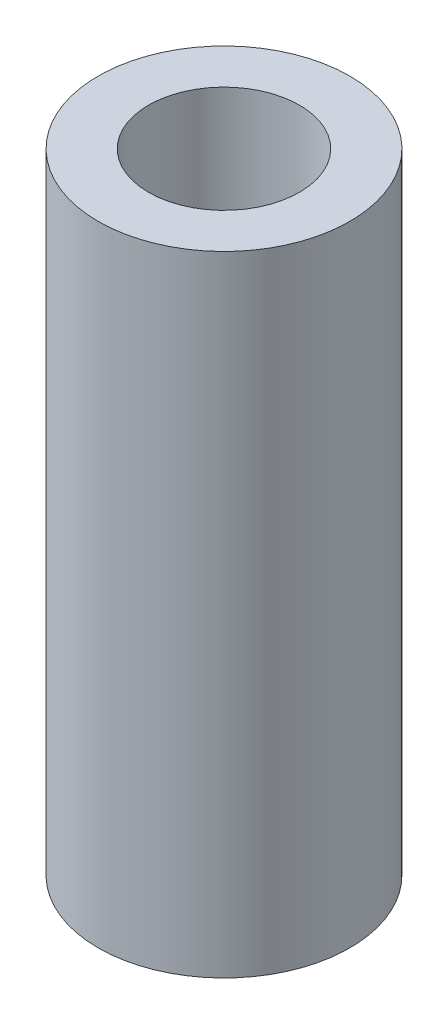
SolidWorks part; units mm, degrees
ref_plane "前视基准面" through (0, 0, 0) normal (0, 0, 1) x (1, 0, 0)
ref_plane "上视基准面" through (0, 0, 0) normal (0, 1, 0) x (1, 0, 0)
ref_plane "右视基准面" through (0, 0, 0) normal (1, 0, 0) x (0, 0, -1)
sketch "Sketch1" plane through (0, 0, 0) normal (0, 1, 0) x (1, 0, 0)
  circle A0 centre (0, 0) radius 3
  circle A1 centre (0, 0) radius 5
extrude "Boss-Extrude1" add sketch "Sketch1" along normal blind 25
